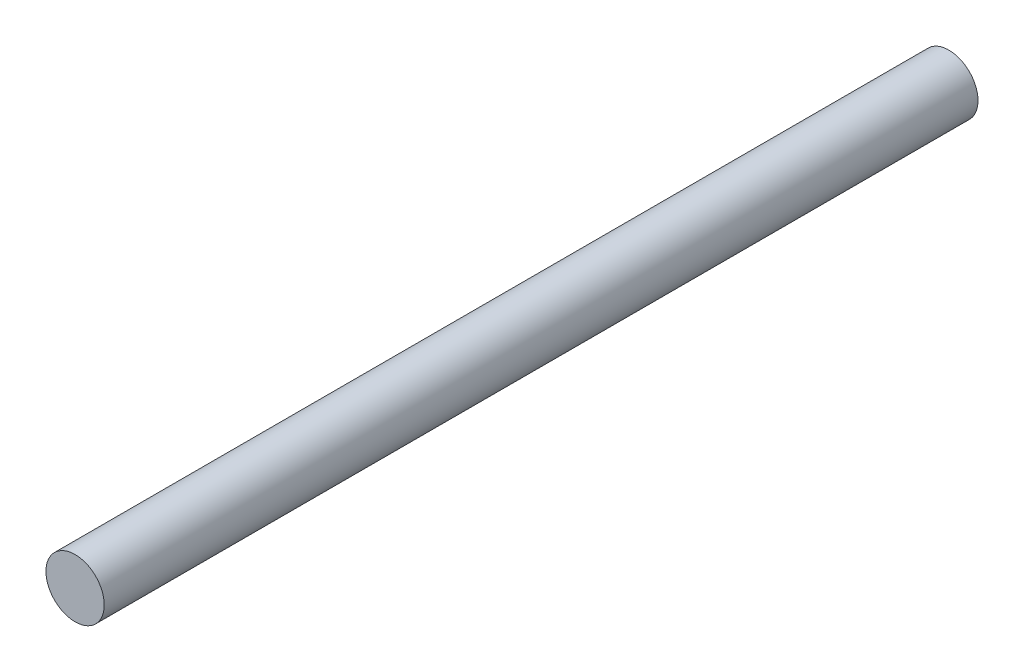
SolidWorks part; units mm, degrees
ref_plane "Front Plane" through (0, 0, 0) normal (0, 0, 1) x (1, 0, 0)
ref_plane "Top Plane" through (0, 0, 0) normal (0, 1, 0) x (1, 0, 0)
ref_plane "Right Plane" through (0, 0, 0) normal (1, 0, 0) x (0, 0, -1)
sketch "Sketch2" plane through (0, 0, 0) normal (0, 0, 1) x (1, 0, 0)
  circle A0 centre (0, 0) radius 1.5875
  dimension "D1" = 3.175
extrude "Boss-Extrude1" add sketch "Sketch2" along normal blind 47.57
